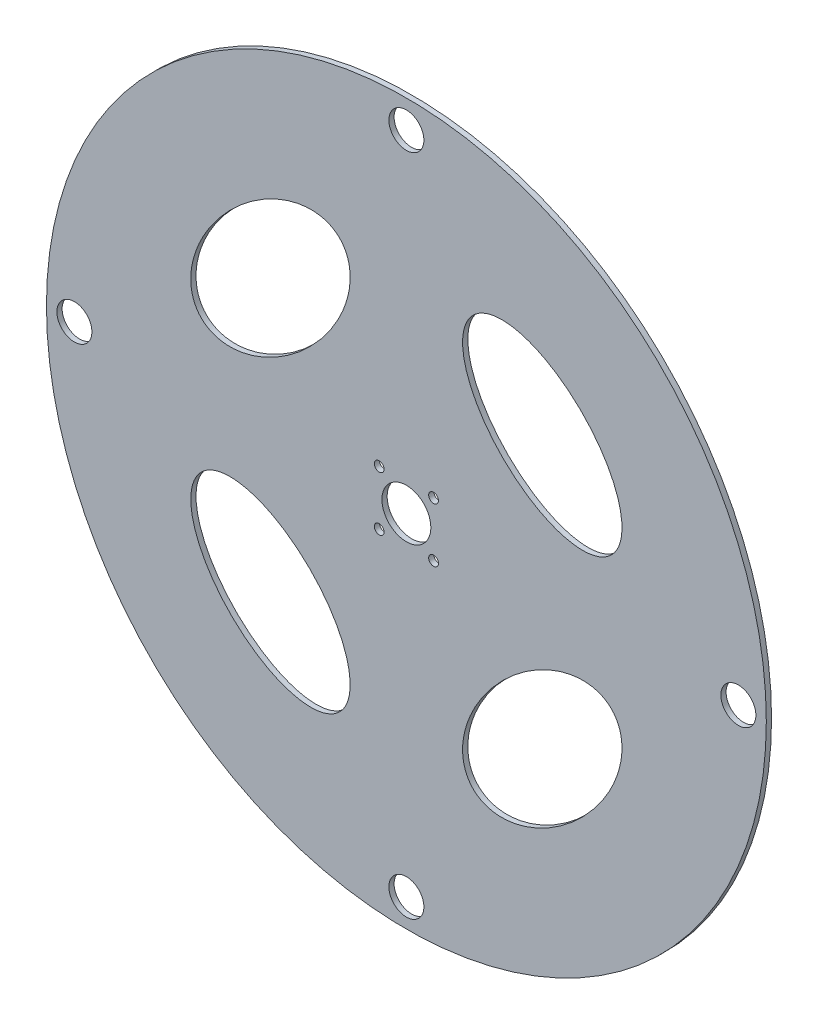
SolidWorks part; units mm, degrees
ref_plane "Front Plane" through (0, 0, 0) normal (0, 0, 1) x (1, 0, 0)
ref_plane "Top Plane" through (0, 0, 0) normal (0, 1, 0) x (1, 0, 0)
ref_plane "Right Plane" through (0, 0, 0) normal (1, 0, 0) x (0, 0, -1)
sketch "Sketch1" plane through (0, 0, 0) normal (0, 0, 1) x (1, 0, 0)
  circle A0 centre (0, 0) radius 103
  dimension "D1" = 206
extrude "Base Disc" add sketch "Sketch1" along normal blind 1.5
sketch "Sketch2" plane through (0, 0, 0) normal (0, 0, -1) x (-1, 0, 0)
  circle A0 centre (0, 0) radius 7.5
sketch "Sketch3" plane through (0, 0, 0) normal (0, 0, -1) x (-1, 0, 0)
  circle A0 centre (95, 0) radius 3
  dimension "D1" = 6
  dimension "D2" = 95
extrude "Cut-Extrude1" cut sketch "Sketch3" against normal through all
sketch "Sketch4" plane through (0, 0, 0) normal (0, 0, -1) x (-1, 0, 0)
  line L0 (0, 0) -> (38.8909, 38.8909) construction
  ellipse E0 centre (38.8909, 38.8909) end of major axis (19.0919, 58.6899) minor radius 16
extrude "Cut-Extrude2" cut sketch "Sketch4" against normal through all
extrude "Cut-Extrude3" cut sketch "Sketch2" against normal through all
pattern_circular "CirPattern3" count 4 over 360 about axis through (0, 0, 0) along (0, 0, 1) of "Cut-Extrude1"
pattern_circular "CirPattern4" count 4 over 360 about axis through (0, 0, 0) along (0, 0, -1) of "Cut-Extrude2"
sketch "Sketch5" plane through (0, 0, 0) normal (0, 0, 1) x (1, 0, 0)
  line L0 (-15.8162, -15.8162) -> (-7.7782, -7.7782) construction
  line L1 (707.1068, -707.1068) -> (-6.7882, 6.7882) construction
  line L2 (-7.7782, 7.7782) -> (-720.1946, 720.1946) construction
  line L3 (-6.7882, -6.7882) -> (7.5537, 7.5537) construction
  circle A1 centre (-7.7782, -7.7782) radius 1.4
  circle A2 centre (-7.7782, 7.7782) radius 1.4
  circle A3 centre (7.7782, 7.7782) radius 1.4
  circle A4 centre (7.7782, -7.7782) radius 1.4
  point P18 (0, 0)
  dimension "D1" = 4
extrude "Cut-Extrude4" cut sketch "Sketch5" along normal through all
sketch "Sketch6" plane through (0, 0, 0) normal (0, 0, 1) x (1, 0, 0)
  circle A0 centre (0, 0) radius 7.51
  circle A1 centre (0, 0) radius 7
extrude "Centre_Bore_Correction_D14" add sketch "Sketch6" along normal blind 1.5
sketch "Sketch7" plane through (0, 0, 0) normal (0, 0, -1) x (-1, 0, 0)
  circle A0 centre (-95, 0) radius 5.01
  circle A1 centre (0, 95) radius 5.01
  circle A2 centre (95, 0) radius 5.01
  circle A3 centre (0, -95) radius 5.01
extrude "RevB_Four_Cartridge_Pilot_Holes_D10p02_R95" cut sketch "Sketch7" against normal through all
